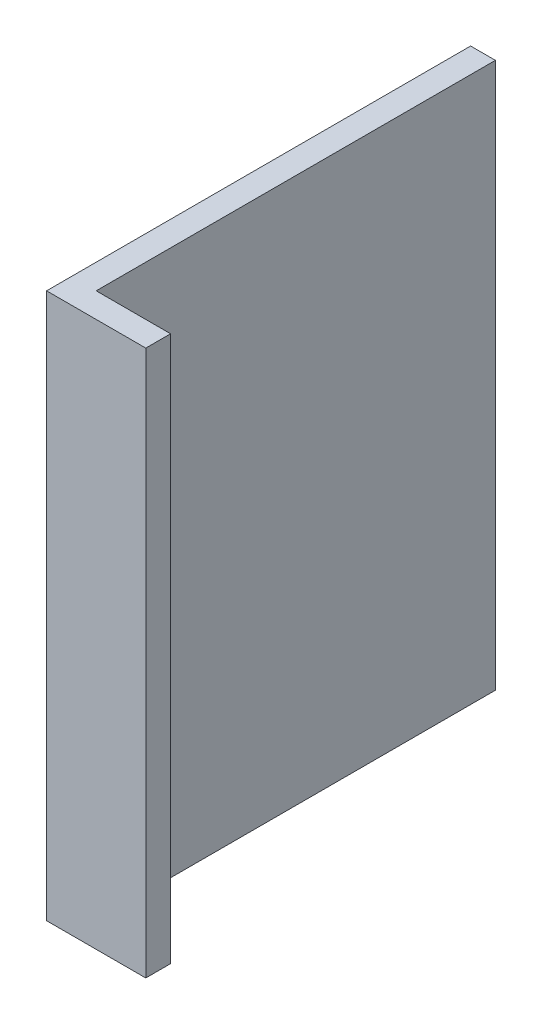
SolidWorks part; units mm, degrees
ref_plane "Front Plane" through (0, 0, 0) normal (0, 0, 1) x (1, 0, 0)
ref_plane "Top Plane" through (0, 0, 0) normal (0, 1, 0) x (1, 0, 0)
ref_plane "Right Plane" through (0, 0, 0) normal (1, 0, 0) x (0, 0, -1)
sketch "Sketch1" plane through (0, 0, 0) normal (0, 1, 0) x (1, 0, 0)
  line L6 (-7.5603, 0) -> (-9.5603, 0)
  line L7 (-9.5603, 0) -> (-9.5603, 8.55)
  line L8 (-9.5603, 8.55) -> (-9.0603, 8.55)
  line L9 (-9.0603, 8.55) -> (-9.0603, 0.5)
  line L10 (-9.0603, 0.5) -> (-7.5603, 0.5)
  line L11 (-7.5603, 0.5) -> (-7.5603, 0)
  dimension "D5" = 8.55
  dimension "D6" = 2
  dimension "D7" = 0.5
extrude "Boss-Extrude1" add sketch "Sketch1" along normal blind 11
